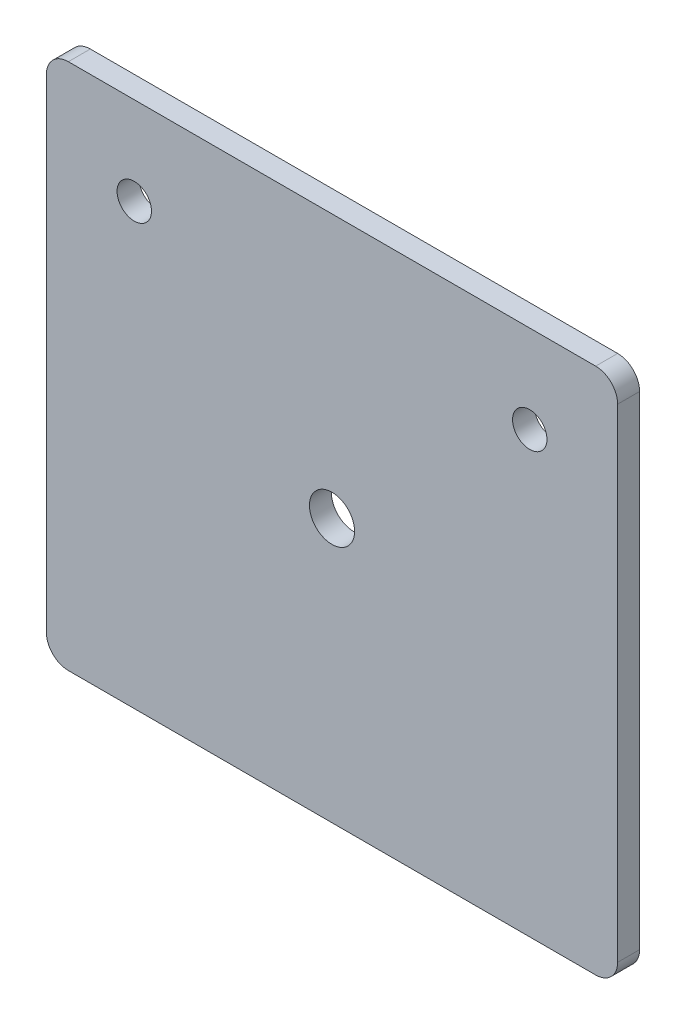
SolidWorks part; units mm, degrees
ref_plane "Front Plane" through (0, 0, 0) normal (0, 0, 1) x (1, 0, 0)
ref_plane "Top Plane" through (0, 0, 0) normal (0, 1, 0) x (1, 0, 0)
ref_plane "Right Plane" through (0, 0, 0) normal (1, 0, 0) x (0, 0, -1)
sketch "Sketch1" plane through (0, 0, 0) normal (0, 0, 1) x (1, 0, 0)
  line L0 (0, 0) -> (0, 24.8747) construction
  line L1 (-41.275, -38.1) -> (41.275, -38.1)
  line L2 (-41.275, -38.1) -> (-41.275, 38.1)
  line L3 (-41.275, 38.1) -> (41.275, 38.1)
  line L4 (41.275, -38.1) -> (41.275, 38.1)
  line L5 (-41.275, -38.1) -> (41.275, 38.1) construction
  line L6 (-41.275, 38.1) -> (41.275, -38.1) construction
  circle A0 centre (-28.575, 25.4) radius 3.175
  circle A2 centre (28.575, 25.4) radius 3.175
  circle A3 centre (0, 0) radius 3.175
  point P0 (0, 0)
  dimension "D5" = 6.35
  dimension "D7" = 6.35
  dimension "D8" = 38.1
  dimension "D1" = 76.2
  dimension "D2" = 82.55
  dimension "D3" = 12.7
  dimension "D4" = 12.7
  dimension "D6" = 12.7
extrude "Boss-Extrude1" add sketch "Sketch1" along normal blind 3.175 contours A0 | L1 L4 L3 L2 A3 A2 A0 | A3 | A2
sketch "Sketch2" plane through (0, 0, 3.175) normal (0, 0, 1) x (1, 0, 0)
  line L0 (-15.875, 38.1) -> (-15.875, 12.7)
  line L2 (-15.875, 12.7) -> (15.875, 12.7)
  line L3 (15.875, 12.7) -> (15.875, 38.1)
  line L4 (15.875, 38.1) -> (-15.875, 38.1)
  line L7 (-41.275, -38.1) -> (-41.275, 38.1) construction
  line L8 (-41.275, 38.1) -> (41.275, 38.1) construction
  dimension "D1" = 31.75
  dimension "D2" = 25.4
  dimension "D3" = 25.4
extrude "Cut-Extrude1" [suppressed] cut sketch "Sketch2" against normal blind 3.175 contours L3 L4 L0 L2
fillet "Fillet1" [suppressed] radius 3.175
hole_wizard "#10 Clearance Hole1" positions "Sketch3" profile "Sketch4" hole size "#10" standard "ANSI Inch" end condition through all
sketch "Sketch3" plane through (0, 0, 3.175) normal (0, 0, 1) x (1, 0, 0)
  circle A0 centre (-28.575, 25.4) radius 3.175 construction
  circle A1 centre (28.575, 25.4) radius 3.175 construction
  point P0 (-28.575, 25.4)
  point P7 (28.575, 25.4)
sketch "Sketch4" plane through (-28.575, 25.4, 3.175) normal (1, 0, 0) x (0, -1, 0)
  line L0 (0, 0) -> (0, 3.175)
  line L1 (0, 3.175) -> (2.4892, 3.175)
  line L2 (2.4892, 3.175) -> (2.4892, 0)
  line L5 (2.4892, 0) -> (0, 0)
  line L11 (0, -6.35) -> (0, 107.95) construction
  dimension "Thru Hole Dia." = 4.9784
  dimension "Thru Hole Depth" = 3.175
hole_wizard "1/4 Clearance Hole1" positions "Sketch7" profile "Sketch8" hole size "1/4" standard "ANSI Inch" end condition through all
sketch "Sketch7" plane through (0, 0, 3.175) normal (0, 0, 1) x (1, 0, 0)
  circle A0 centre (0, 0) radius 3.175 construction
  point P0 (0, 0)
sketch "Sketch8" plane through (0, 0, 3.175) normal (1, 0, 0) x (0, -1, 0)
  line L0 (0, 0) -> (0, 3.175)
  line L1 (0, 3.175) -> (3.2639, 3.175)
  line L2 (3.2639, 3.175) -> (3.2639, 0)
  line L5 (3.2639, 0) -> (0, 0)
  line L11 (0, -6.35) -> (0, 107.95) construction
  dimension "Thru Hole Dia." = 6.5278
  dimension "Thru Hole Depth" = 3.175
fillet "Fillet2" radius 3.175 4 edges at (-41.275, -38.1, 1.5875) (-41.275, 38.1, 1.5875) (41.275, -38.1, 1.5875) (41.275, 38.1, 1.5875)
